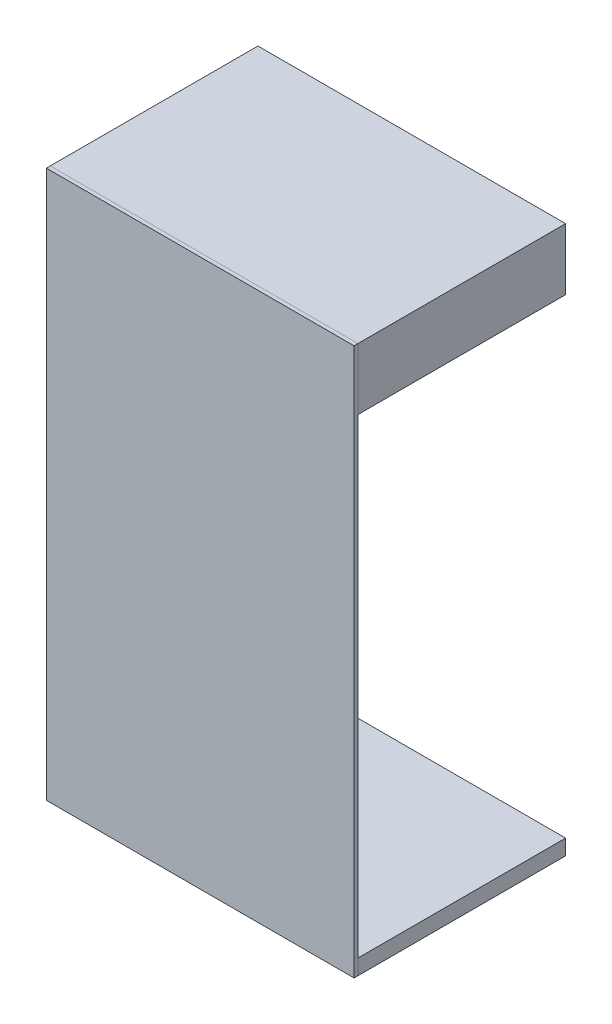
SolidWorks part; units mm, degrees
ref_plane "Спереди" through (0, 0, 0) normal (0, 0, 1) x (1, 0, 0)
ref_plane "Сверху" through (0, 0, 0) normal (0, 1, 0) x (1, 0, 0)
ref_plane "Справа" through (0, 0, 0) normal (1, 0, 0) x (0, 0, -1)
sketch "Эскиз1" plane through (0, 0, 0) normal (0, 0, 1) x (1, 0, 0)
  line L0 (-8127, -7118) -> (-8127, 0) construction
  line L1 (-8127, -7118) -> (-12127, -7118)
  line L2 (-8127, -7118) -> (-8127, 0)
  line L3 (-8127, 0) -> (-12127, 0)
  line L4 (-12127, -7118) -> (-12127, 0)
  dimension "D1" = 4000
extrude "Бобышка-Вытянуть1" add sketch "Эскиз1" against normal blind 50 contours L4 L3 L2 L1
sketch "Эскиз2" plane through (0, 0, -50) normal (0, 0, -1) x (-1, 0, 0)
  line L0 (8127, -800) -> (8127, 0)
  line L1 (8127, -7118) -> (8127, 0) construction
  line L2 (8127, 0) -> (12127, 0)
  line L3 (12127, 0) -> (12127, -7118)
  line L4 (12127, -7118) -> (8127, -7118)
  line L6 (8327, -800) -> (8327, -200)
  line L7 (8327, -200) -> (11927, -200)
  line L8 (11927, -200) -> (11927, -6918)
  line L9 (11927, -6918) -> (8127, -6918)
  line L11 (8127, -800) -> (8327, -800)
  line L13 (8127, -7118) -> (8075.3297, -7118) construction
  line L14 (8127, -6918) -> (8075.3297, -6918) construction
  line L15 (8127, -7118) -> (8127, -6918)
  dimension "D3" = 800
  dimension "D1" = 200
extrude "Бобышка-Вытянуть2" add sketch "Эскиз2" along normal blind 2700 separate body
